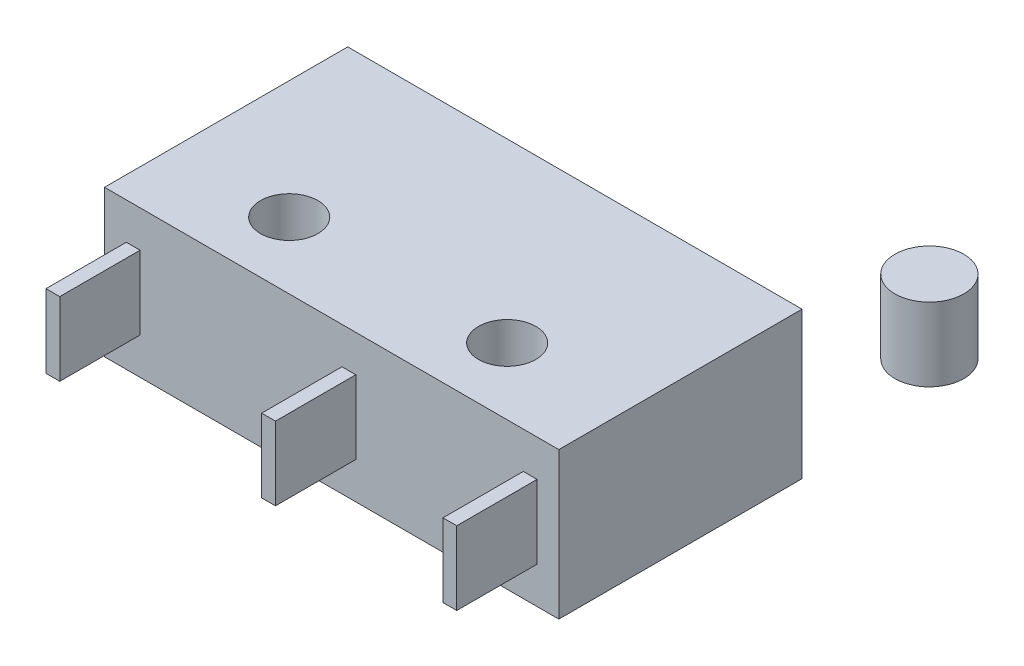
SolidWorks part; units mm, degrees
ref_plane "Front Plane" through (0, 0, 0) normal (0, 0, 1) x (1, 0, 0)
ref_plane "Top Plane" through (0, 0, 0) normal (0, 1, 0) x (1, 0, 0)
ref_plane "Right Plane" through (0, 0, 0) normal (1, 0, 0) x (0, 0, -1)
sketch "Sketch1" plane through (0, 0, 0) normal (0, 1, 0) x (1, 0, 0)
  line L0 (13.3357, 9.564) -> (33.1357, 9.564) construction
  line L1 (13.3357, 17.264) -> (33.1357, 17.264)
  line L2 (13.3357, 17.264) -> (13.3357, 6.664)
  line L3 (13.3357, 6.664) -> (33.1357, 6.664)
  line L4 (33.1357, 17.264) -> (33.1357, 6.664)
  line L5 (18.4857, 9.564) -> (18.4857, 17.264) construction
  line L6 (19.4857, 17.264) -> (21.4857, 17.264)
  circle A0 centre (18.4857, 9.564) radius 1.25
  circle A1 centre (27.9857, 9.564) radius 1.25
  dimension "D4" = 2.5
  dimension "D5" = 2.5
  dimension "D6" = 9.5
  dimension "D7" = 5.15
  dimension "D1" = 19.8
  dimension "D2" = 10.6
  dimension "D3" = 2.9
extrude "Boss-Extrude1" add sketch "Sketch1" along normal blind 6.4
sketch "Sketch2" plane through (0, 6.4, 0) normal (0, 1, 0) x (1, 0, 0)
  line L0 (32.9857, 24.464) -> (32.9857, 22.964) construction
  line L2 (18.4857, 9.564) -> (18.4857, 24.464) construction
  line L3 (18.4857, 24.464) -> (32.9857, 24.464) construction
  circle A0 centre (32.9857, 22.964) radius 1.5
  dimension "D4" = 3
  dimension "D1" = 1.5
  dimension "D2" = 14.5
  dimension "D3" = 14.9
sketch "Sketch3" plane through (0, 6.4, 0) normal (0, 1, 0) x (1, 0, 0)
  line L0 (14.2857, 6.664) -> (14.2857, 3.164)
  line L1 (13.3357, 6.664) -> (33.1357, 6.664) construction
  line L2 (14.2857, 3.164) -> (14.8857, 3.164)
  line L3 (14.8857, 3.164) -> (14.8857, 6.664)
  line L4 (23.6857, 6.664) -> (23.6857, 3.164)
  line L5 (23.6857, 3.164) -> (24.2869, 3.164)
  line L6 (24.2869, 3.164) -> (24.2869, 6.664)
  line L7 (31.5869, 6.664) -> (31.5869, 3.164)
  line L8 (31.5869, 3.164) -> (32.1869, 3.164)
  line L9 (32.1869, 3.164) -> (32.1869, 6.664)
  line L10 (13.3357, 17.264) -> (13.3357, 6.664) construction
  line L11 (33.1357, 17.264) -> (33.1357, 6.664) construction
  line M20 (13.3357, 6.664) -> (33.1357, 6.664)
  dimension "D1" = 3.5
  dimension "D2" = 0.6
  dimension "D3" = 0.6012
  dimension "D4" = 8.8
  dimension "D5" = 0.6
  dimension "D6" = 7.3
  dimension "D7" = 0.95
  dimension "D8" = 0.9488
extrude "Boss-Extrude2" add sketch "Sketch3" against normal blind 3.2 from offset 1.6 contours L2 L3 L0 M20 | L5 L6 L4 M20 | L8 L9 L7 M20 offset against normal yes
sketch "Sketch4" plane through (0, 0, 0) normal (0, -1, 0) x (1, 0, 0)
  line L1 (19.4857, -18.564) -> (21.4857, -18.564)
  line L2 (19.4857, -18.564) -> (19.4857, -17.264)
  line L3 (19.4857, -17.264) -> (21.4857, -17.264)
  line L4 (21.4857, -18.564) -> (21.4857, -17.264)
  circle A0 centre (32.9857, -22.964) radius 1.5
  circle A1 centre (18.4857, -9.564) radius 1.25 construction
  circle A2 centre (27.9857, -9.564) radius 1.25 construction
  dimension "D3" = 1
  dimension "D4" = 3
  dimension "D5" = 13.4
  dimension "D1" = 2
  dimension "D2" = 9
extrude "Boss-Extrude4" add sketch "Sketch4" against normal blind 3.2 from offset 1.6 offset against normal yes
